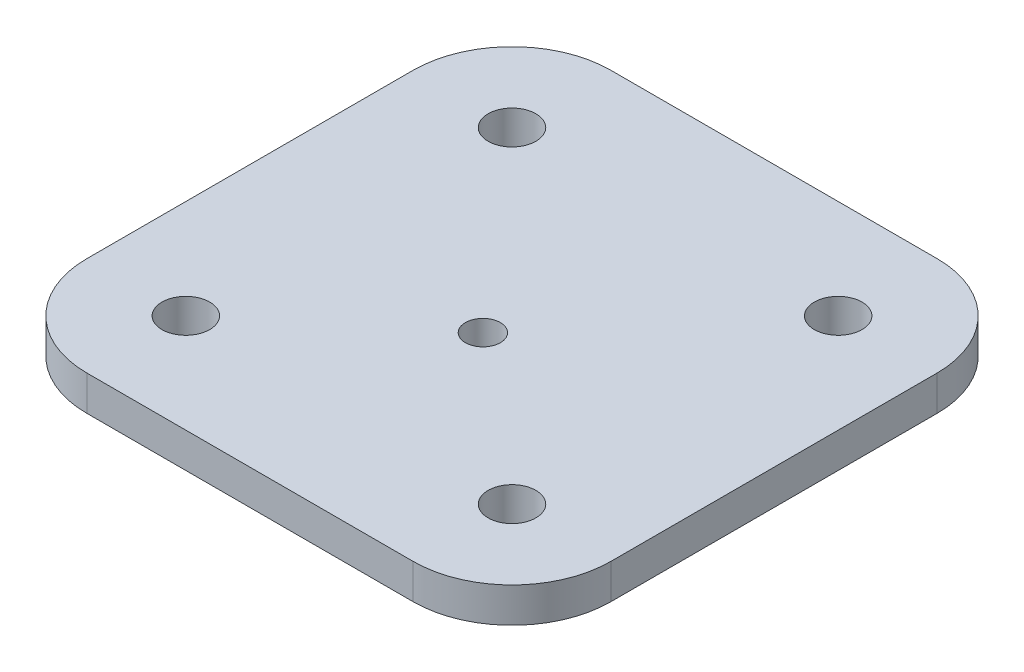
SolidWorks part; units mm, degrees
ref_plane "Спереди" through (0, 0, 0) normal (0, 0, 1) x (1, 0, 0)
ref_plane "Сверху" through (0, 0, 0) normal (0, 1, 0) x (1, 0, 0)
ref_plane "Справа" through (0, 0, 0) normal (1, 0, 0) x (0, 0, -1)
sketch "Эскиз1" plane through (0, 0, 0) normal (0, 1, 0) x (1, 0, 0)
  line L1 (-14, -22.5) -> (14, -22.5)
  line L2 (-22.5, -14) -> (-22.5, 14)
  line L3 (-14, 22.5) -> (14, 22.5)
  line L4 (22.5, -14) -> (22.5, 14)
  line L5 (-22.5, -22.5) -> (22.5, 22.5) construction
  line L6 (-22.5, 22.5) -> (22.5, -22.5) construction
  circle A0 centre (14, 14) radius 2.05
  circle A1 centre (14, -14) radius 2.05
  circle A2 centre (-14, -14) radius 2.05
  circle A3 centre (-14, 14) radius 2.05
  arc A4 (-22.5, -14) -> (-14, -22.5) centre (-14, -14) ccw
  arc A5 (14, -22.5) -> (22.5, -14) centre (14, -14) ccw
  arc A6 (22.5, 14) -> (14, 22.5) centre (14, 14) ccw
  arc A7 (-14, 22.5) -> (-22.5, 14) centre (-14, 14) ccw
  point P0 (0, 0)
  point P14 (0, 0)
  point P15 (0, 0)
  point P16 (0, 0)
  point P17 (0, 0)
  point P20 (7.7187, 12.6277)
  point P21 (32.8704, -11.5202)
  dimension "D3" = 4.1
  dimension "D8" = 8.5
  dimension "D1" = 45
  dimension "D2" = 45
  dimension "D4" = 28
  dimension "D5" = 28
  dimension "D6" = 14
  dimension "D7" = 14
extrude "Бобышка-Вытянуть1" add sketch "Эскиз1" along normal blind 3
sketch "Эскиз2" plane through (0, 0, 0) normal (0, -1, 0) x (1, 0, 0)
  line L0 (14, -22.5) -> (-14, -22.5) construction
  circle A0 centre (0, 2.5) radius 1.5
  point P4 (0, 0)
  dimension "D1" = 3
  dimension "D2" = 25
extrude "Вырез-Вытянуть1" cut sketch "Эскиз2" against normal blind 3
